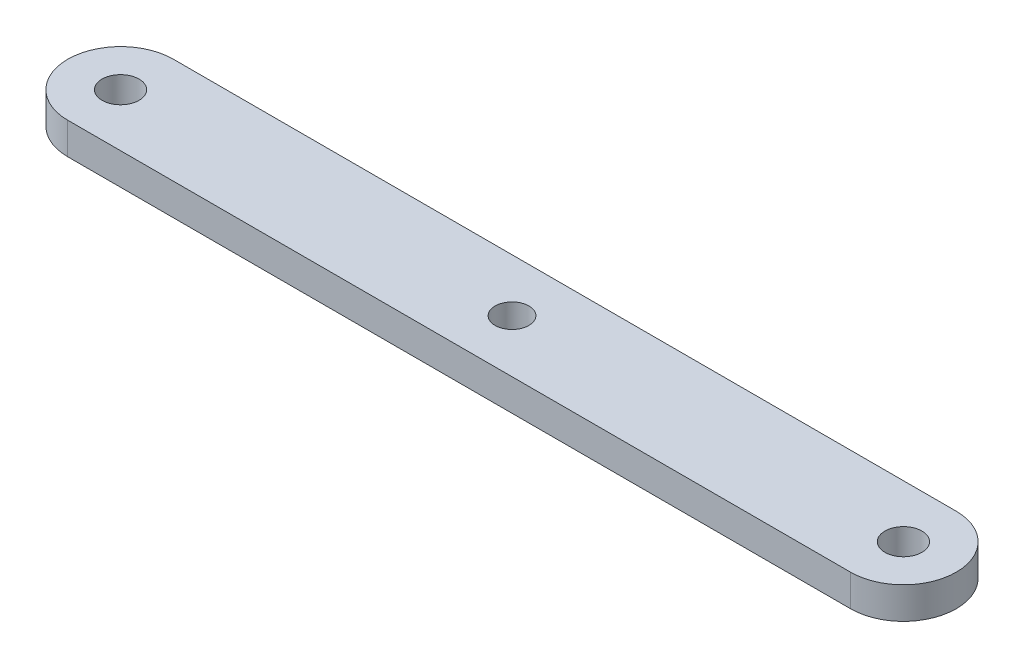
SolidWorks part; units mm, degrees
ref_plane "Front Plane" through (0, 0, 0) normal (0, 0, 1) x (1, 0, 0)
ref_plane "Top Plane" through (0, 0, 0) normal (0, 1, 0) x (1, 0, 0)
ref_plane "Right Plane" through (0, 0, 0) normal (1, 0, 0) x (0, 0, -1)
sketch "Sketch1" plane through (0, 0, 0) normal (0, 1, 0) x (1, 0, 0)
  line L0 (-45, 0) -> (45, 0) construction
  line L1 (0, 0) -> (0, -141.54) construction
  line L2 (0, -141.54) -> (-45, 0) construction
  line L3 (45, 0) -> (0, -141.54) construction
  line L4 (37.0517, -25) -> (-37.0517, -25) construction
  line L5 (-37.0517, -25) -> (37.0517, -25) construction
  line L6 (-37.0517, -20) -> (37.0517, -20)
  line L7 (-37.0517, -30) -> (37.0517, -30)
  line L8 (-45, 0) -> (45, 0) construction
  line L9 (-45, 5) -> (45, 5) construction
  line L10 (-45, -5) -> (45, -5) construction
  arc A0 (-37.0517, -20) -> (-37.0517, -30) centre (-37.0517, -25) ccw
  arc A1 (37.0517, -30) -> (37.0517, -20) centre (37.0517, -25) ccw
  arc A2 (-45, 5) -> (-45, -5) centre (-45, 0) ccw construction
  arc A3 (45, -5) -> (45, 5) centre (45, 0) ccw construction
  circle A4 centre (0, -25) radius 1.6
  circle A5 centre (37.0517, -25) radius 1.75
  circle A6 centre (-37.0517, -25) radius 1.75
  circle A7 centre (45, 0) radius 2 construction
  circle A8 centre (-45, 0) radius 2 construction
  point P5 (0, -25)
  point P8 (0, -25)
  point P13 (0, 0)
  dimension "D4" = 5
  dimension "D5" = 5
  dimension "D6" = 3.2
  dimension "D7" = 3.5
  dimension "D8" = 4
  dimension "D1" = 90
  dimension "D2" = 141.54
  dimension "D3" = 25
extrude "Boss-Extrude1" add sketch "Sketch1" along normal blind 3
